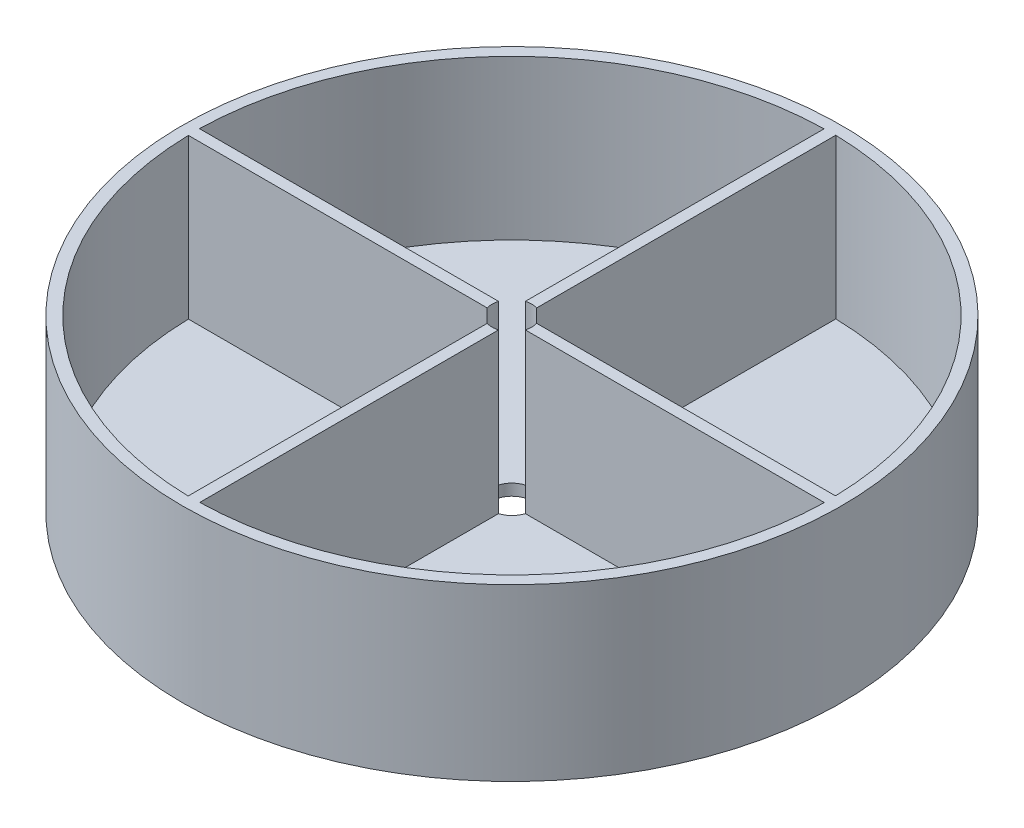
SolidWorks part; units mm, degrees
ref_plane "Plan de face" through (0, 0, 0) normal (0, 0, 1) x (1, 0, 0)
ref_plane "Plan de dessus" through (0, 0, 0) normal (0, 1, 0) x (1, 0, 0)
ref_plane "Plan de droite" through (0, 0, 0) normal (1, 0, 0) x (0, 0, -1)
sketch "Esquisse2" plane through (0, 0, 0) normal (0, 1, 0) x (1, 0, 0)
  circle A0 centre (0, 0) radius 58
extrude "Boss.-Extru.2" add sketch "Esquisse2" along normal blind 30
sketch "Esquisse3" plane through (0, 30, 0) normal (0, 1, 0) x (1, 0, 0)
  line L25 (-55.9914, 1) -> (-1, 1)
  line L26 (-1, 1) -> (-1, 55.9409)
  arc A1 (-55.9914, 1) -> (-1, 55.9409) centre (0.1777, -0.2293) cw
  point P31 (-1, 1)
  point P32 (-39.5235, 39.5235)
  point P33 (-1, 55.9409)
  point P34 (-55.9914, 1)
extrude "Enlèv. mat.-Extru.2" cut sketch "Esquisse3" against normal blind 28 contours L25 L26 A1
sketch "Esquisse5" plane through (0, 30, 0) normal (0, 1, 0) x (1, 0, 0)
  line L0 (1, 55.9914) -> (1, 1)
  line L1 (1, 1) -> (55.9409, 1)
  line L2 (-1, 30.1428) -> (1, 30.1428)
  line L3 (-1, 1) -> (-1, 55.9409) construction
  line L4 (-55.9914, 1) -> (57.9914, 1)
  line L5 (1, 30.1428) -> (1, 1)
  arc A0 (1, 55.9914) -> (55.9409, 1) centre (-0.2294, -0.1777) cw
  circle A1 centre (0, 0) radius 58 construction
  point P15 (1, 1)
extrude "Enlèv. mat.-Extru.3" cut sketch "Esquisse5" against normal blind 28 contours L0 L1 A0
sketch "Esquisse14" plane through (0, 30, 0) normal (0, 1, 0) x (1, 0, 0)
  line L3 (-1, 1) -> (-1, -57.9914)
  line L4 (-55.9914, 1) -> (-1, 1) construction
  line L5 (-12.3257, 1) -> (-12.3257, -1)
  line L9 (-12.3257, -1) -> (-0.2906, -1)
  line L25 (-1, -55.9914) -> (-1, -1)
  line L26 (-1, -1) -> (-55.9409, -1)
  circle A0 centre (0, 0) radius 58 construction
  arc A1 (-1, -55.9914) -> (-55.9409, -1) centre (0.2293, 0.1777) cw
  point P9 (-12.3257, -1)
  point P10 (-1, -1)
  point P31 (13.5876, -76.6665)
  point P32 (-24.9359, -38.143)
  point P33 (34.4497, 18.9628)
  point P34 (-20.5417, -35.978)
extrude "Enlèv. mat.-Extru.8" cut sketch "Esquisse14" against normal blind 28 contours L25 L26 A1
sketch "Esquisse17" plane through (0, 30, 0) normal (0, 1, 0) x (1, 0, 0)
  line L25 (55.9914, -1) -> (1, -1)
  line L26 (1, -1) -> (1, -55.9409)
  arc A1 (55.9914, -1) -> (1, -55.9409) centre (-0.1777, 0.2294) cw
  point P6 (1, -1)
  point P31 (70.6995, -65.1258)
  point P32 (32.176, -26.6023)
  point P33 (70.6995, -10.1849)
  point P34 (15.7081, -65.1258)
extrude "Enlèv. mat.-Extru.10" cut sketch "Esquisse17" against normal blind 28 contours L25 L26 A1
sketch "Esquisse18" plane through (0, 0, 0) normal (0, -1, 0) x (1, 0, 0)
  circle A0 centre (0, 0) radius 3
extrude "Enlèv. mat.-Extru.11" cut sketch "Esquisse18" against normal blind 30
sketch "Esquisse21" plane through (0, 2, 0) normal (0, 1, 0) x (1, 0, 0)
  circle A0 centre (0, 0) radius 3.5
extrude "Enlèv. mat.-Extru.13" cut sketch "Esquisse21" along normal up to vertex (28 mm away) contours A0
sketch "Esquisse22" plane through (0, 2, 0) normal (0, 1, 0) x (1, 0, 0)
  circle A0 centre (0, 0) radius 3.5
extrude "Enlèv. mat.-Extru.14" cut sketch "Esquisse22" against normal blind 10
